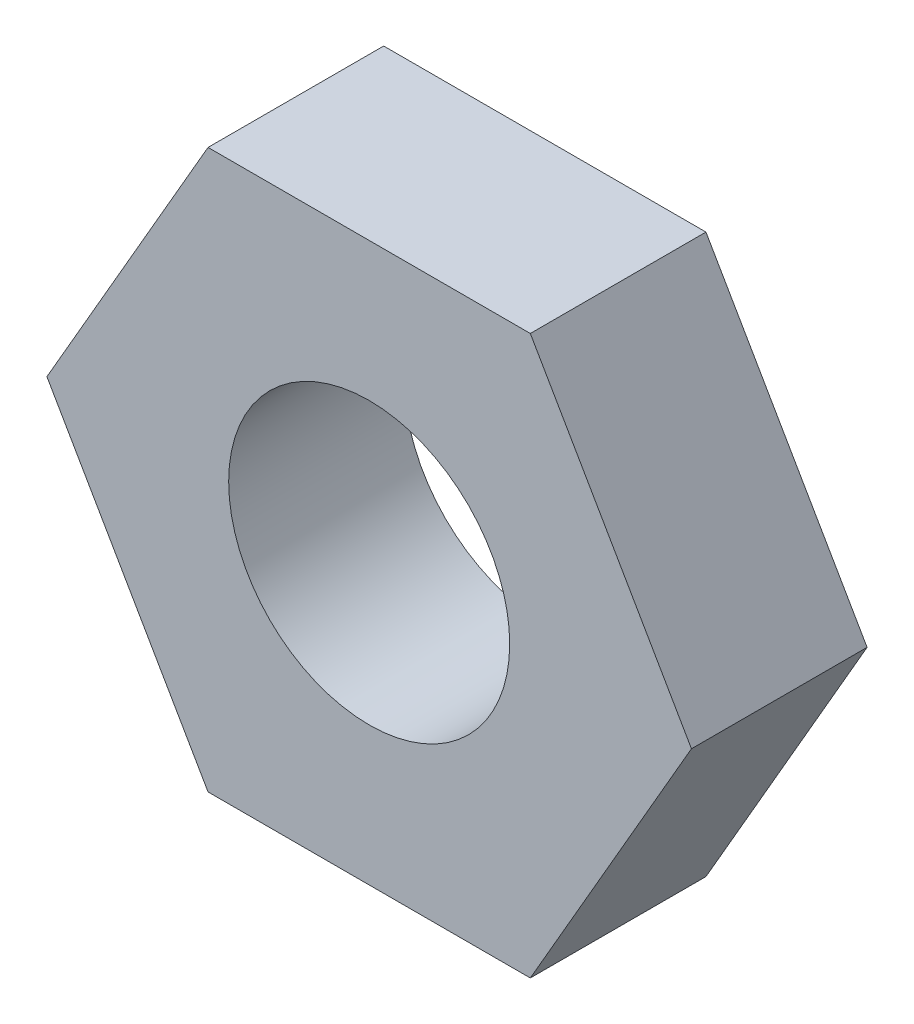
SolidWorks part; units mm, degrees
material "1023 Carbon Steel Sheet (SS)"
ref_plane "Ebene vorne" through (0, 0, 0) normal (0, 0, 1) x (1, 0, 0)
ref_plane "Ebene oben" through (0, 0, 0) normal (0, 1, 0) x (1, 0, 0)
ref_plane "Ebene rechts" through (0, 0, 0) normal (1, 0, 0) x (0, 0, -1)
sketch "Sketch1" plane through (0, 0, 0) normal (0, 0, 1) x (1, 0, 0)
  line L0 (-4.587, 7.945) -> (-6.8806, 3.9725)
  line L1 (-6.8806, 3.9725) -> (-9.1741, 0)
  line L2 (-9.1741, 0) -> (-6.8806, -3.9725)
  line L3 (-6.8806, -3.9725) -> (-4.587, -7.945)
  line L4 (-4.587, -7.945) -> (0, -7.945)
  line L5 (0, -7.945) -> (4.587, -7.945)
  line L6 (4.587, -7.945) -> (6.8806, -3.9725)
  line L7 (6.8806, -3.9725) -> (9.1741, 0)
  line L8 (9.1741, 0) -> (6.8806, 3.9725)
  line L9 (6.8806, 3.9725) -> (4.587, 7.945)
  line L10 (4.587, 7.945) -> (0, 7.945)
  line L11 (0, 7.945) -> (-4.587, 7.945)
  circle A0 centre (0, 0) radius 7.945 construction
  circle A1 centre (0, 0) radius 4
  dimension "D1" = 15.89
  dimension "D2" = 8
extrude "Boss-Extrude1" add sketch "Sketch1" along normal blind 5
